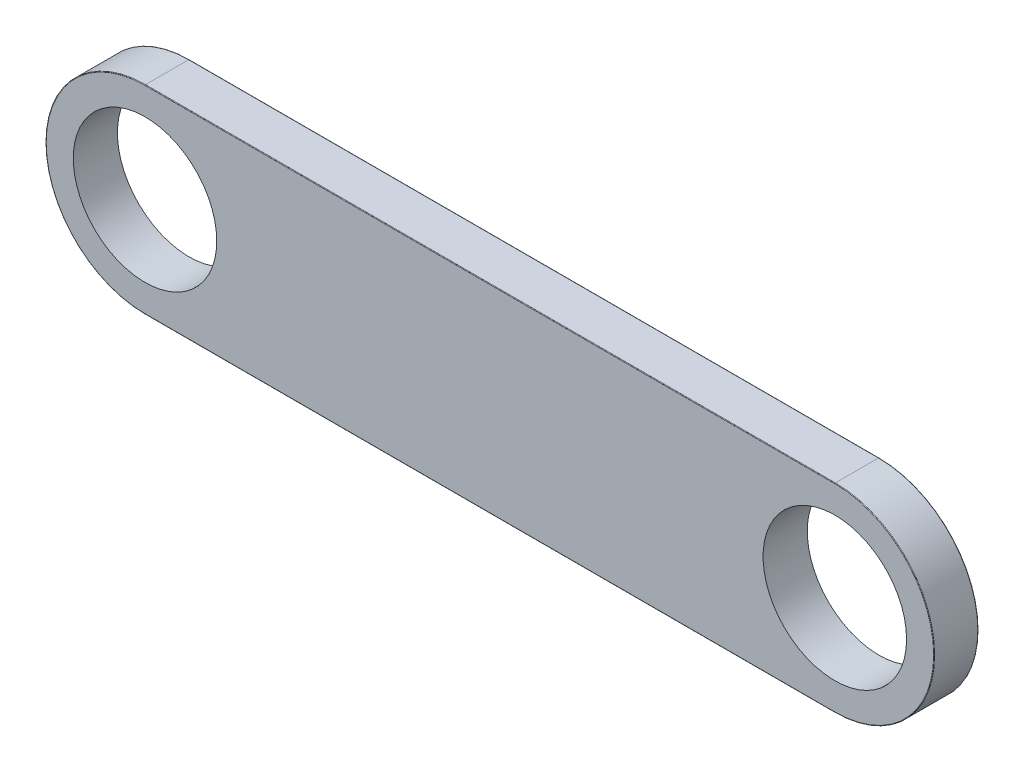
SolidWorks part; units mm, degrees
ref_plane "Front Plane" through (0, 0, 0) normal (0, 0, 1) x (1, 0, 0)
ref_plane "Top Plane" through (0, 0, 0) normal (0, 1, 0) x (1, 0, 0)
ref_plane "Right Plane" through (0, 0, 0) normal (1, 0, 0) x (0, 0, -1)
sketch "Sketch1" plane through (0, 0, 0) normal (0, 0, 1) x (1, 0, 0)
  line L0 (0, 0) -> (125, 0) construction
  line L1 (0, 18) -> (125, 18)
  line L2 (0, -18) -> (125, -18)
  arc A0 (0, 18) -> (0, -18) centre (0, 0) ccw
  arc A1 (125, -18) -> (125, 18) centre (125, 0) ccw
  circle A2 centre (0, 0) radius 13
  circle A3 centre (125, 0) radius 13
  point P3 (62.5, 0)
  dimension "D1" = 18
  dimension "D2" = 26
  dimension "D3" = 125
extrude "Boss-Extrude1" add sketch "Sketch1" along normal blind 8
fillet "Fillet1" radius 0.1 8 edges at (143, 0, 0) (62.5, -18, 0) (-18, 0, 0) (143, 0, 8) (62.5, -18, 8) (-18, 0, 8) (62.5, 18, 0) (62.5, 18, 8)
